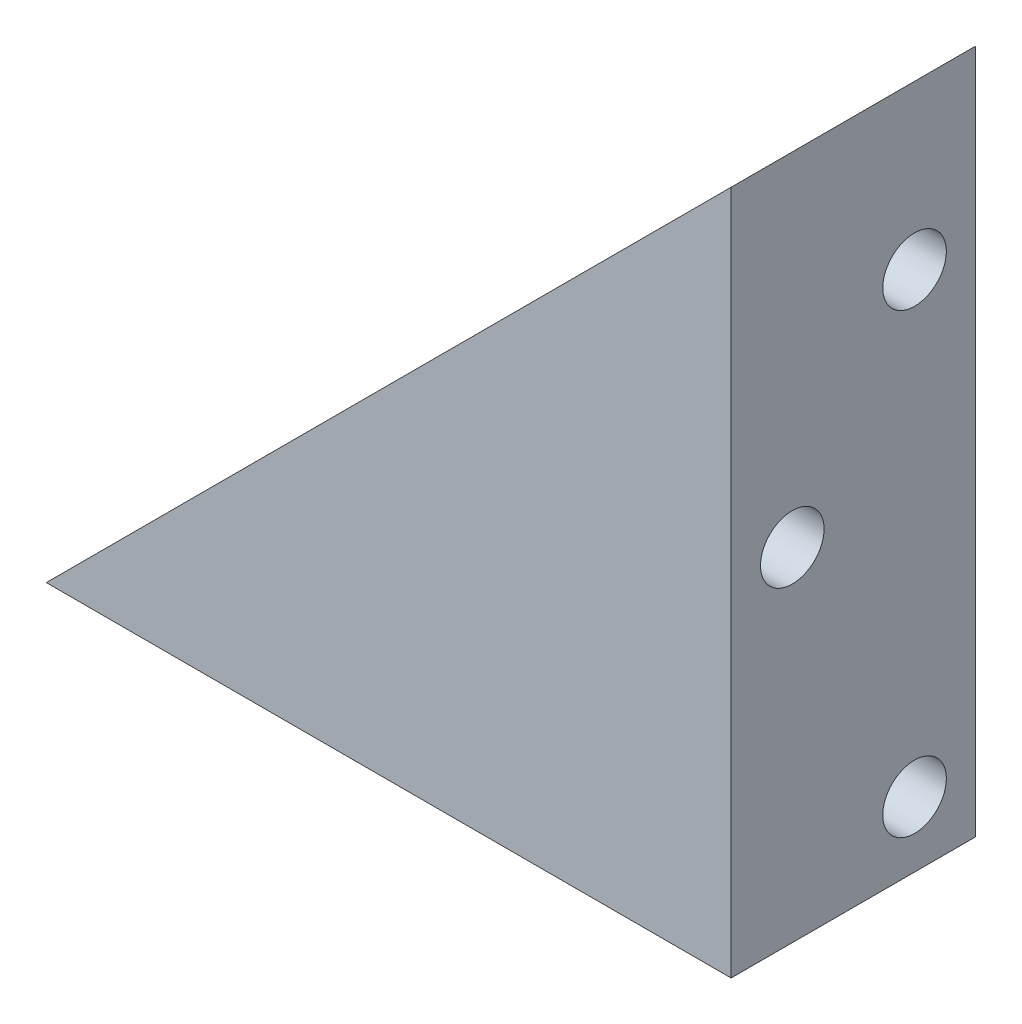
SolidWorks part; units mm, degrees
ref_plane "Front Plane" through (0, 0, 0) normal (0, 0, 1) x (1, 0, 0)
ref_plane "Top Plane" through (0, 0, 0) normal (0, 1, 0) x (1, 0, 0)
ref_plane "Right Plane" through (0, 0, 0) normal (1, 0, 0) x (0, 0, -1)
sketch "Sketch1" plane through (0, 0, 0) normal (0, 0, 1) x (1, 0, 0)
  line L0 (0, 0) -> (42, 0)
  line L1 (42, 0) -> (42, 42)
  line L2 (42, 42) -> (0, 0)
  dimension "D1" = 42
  dimension "D2" = 42
extrude "Boss-Extrude1" add sketch "Sketch1" along normal blind 15
sketch "Sketch3" plane through (0, 0, 0) normal (-0.7071, 0.7071, 0) x (0, 0, 1)
  line L0 (7.5, 59.397) -> (7.5, 0) construction
  line L1 (15, 59.397) -> (0, 59.397) construction
  line L2 (15, 0) -> (0, 0) construction
  line L3 (0, 29.6985) -> (15, 29.6985) construction
  line L4 (0, 59.397) -> (0, 0) construction
  line L5 (15, 59.397) -> (15, 0) construction
  circle A0 centre (7.5, 29.6985) radius 2
  dimension "D1" = 4
extrude "Cut-Extrude1" cut sketch "Sketch3" against normal blind 20
sketch "Sketch4" plane through (42, 0, 0) normal (1, 0, 0) x (0, 0, -1)
  line L0 (-7.5, 0) -> (-7.5, 42) construction
  line L1 (-15, 0) -> (0, 0) construction
  line L2 (-15, 42) -> (0, 42) construction
  line L3 (0, 21) -> (-15, 21) construction
  line L6 (0, 0) -> (0, 42) construction
  line L7 (-15, 0) -> (-15, 42) construction
  line L8 (-7.5, 0) -> (0, 0) construction
  circle A0 centre (-11.25, 21) radius 1.95
  circle A1 centre (-3.75, 4) radius 1.95
  circle A2 centre (-3.75, 32) radius 1.95
  point P12 (-7.5, 21)
  dimension "D1" = 3.9
  dimension "D4" = 3.9
  dimension "D7" = 3.9
  dimension "D2" = 3.75
  dimension "D3" = 21
  dimension "D5" = 4
  dimension "D6" = 3.75
  dimension "D8" = 10
  dimension "D9" = 3.75
extrude "Cut-Extrude2" cut sketch "Sketch4" against normal blind 5.4
